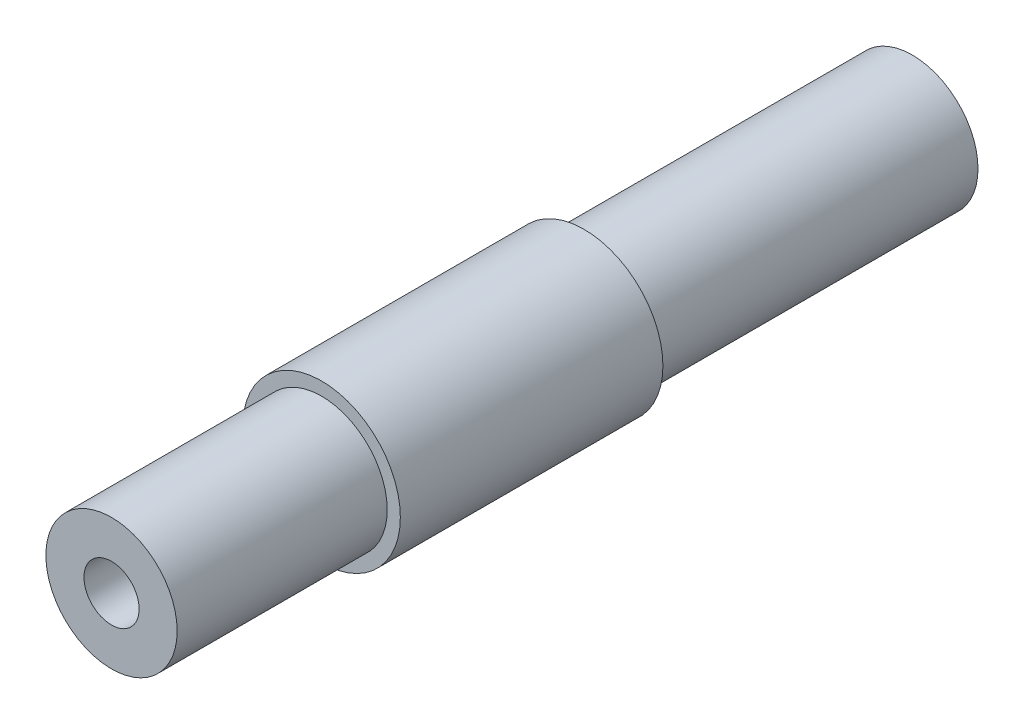
SolidWorks part; units mm, degrees
material "SKD11淬火HRC56-60"
ref_plane "前基準面" through (0, 0, 0) normal (0, 0, 1) x (1, 0, 0)
ref_plane "上基準面" through (0, 0, 0) normal (0, 1, 0) x (1, 0, 0)
ref_plane "右基準面" through (0, 0, 0) normal (1, 0, 0) x (0, 0, -1)
sketch "草图1" plane through (0, 0, 0) normal (0, 0, 1) x (1, 0, 0)
  circle A0 centre (0, 0) radius 6
  dimension "D1" = 12
extrude "凸台-拉伸1" add sketch "草图1" along normal blind 20
sketch "草图2" plane through (0, 0, 20) normal (0, 0, 1) x (1, 0, 0)
  circle A0 centre (0, 0) radius 5
  dimension "D1" = 10
extrude "凸台-拉伸2" add sketch "草图2" along normal blind 16
sketch "草图3" plane through (0, 0, 0) normal (0, 0, -1) x (-1, 0, 0)
  circle A0 centre (0, 0) radius 5
  dimension "D1" = 10
extrude "凸台-拉伸3" add sketch "草图3" along normal blind 25
hole_wizard "M5 螺纹孔1" positions "草图5" profile "草图4" tap size "M5" standard "ISO"
sketch "草图5" plane through (0, 0, -25) normal (0, 0, -1) x (-1, 0, 0)
  point P0 (0, 0)
sketch "草图4" plane through (0, 0, -25) normal (1, 0, 0) x (0, 1, 0)
  line L0 (0, 0) -> (0, 13.6618)
  line L1 (0, 13.6618) -> (2.1, 12.4)
  line L2 (2.1, 12.4) -> (2.1, 0)
  line L5 (2.1, 0) -> (0, 0)
  line L10 (0, 13.6618) -> (-2.1, 12.4) construction
  line L11 (0, -6.35) -> (0, 107.95) construction
  dimension "螺纹孔钻头直径" = 4.2
  dimension "螺纹孔钻头深度" = 12.4
  dimension "导头角度" = 118
cosmetic thread "孔螺蚊线1" parameters "D1"=10, "D2"=5
hole_wizard "M5 螺纹孔2" positions "草图7" profile "草图6" tap size "M5" standard "ISO"
sketch "草图7" plane through (0, 0, 36) normal (0, 0, 1) x (1, 0, 0)
  point P0 (0, 0)
sketch "草图6" plane through (0, 0, 36) normal (1, 0, 0) x (0, -1, 0)
  line L0 (0, 0) -> (0, 13.6618)
  line L1 (0, 13.6618) -> (2.1, 12.4)
  line L2 (2.1, 12.4) -> (2.1, 0)
  line L5 (2.1, 0) -> (0, 0)
  line L10 (0, 13.6618) -> (-2.1, 12.4) construction
  line L11 (0, -6.35) -> (0, 107.95) construction
  dimension "螺纹孔钻头直径" = 4.2
  dimension "螺纹孔钻头深度" = 12.4
  dimension "导头角度" = 118
cosmetic thread "孔螺蚊线2" parameters "D1"=10, "D2"=5
